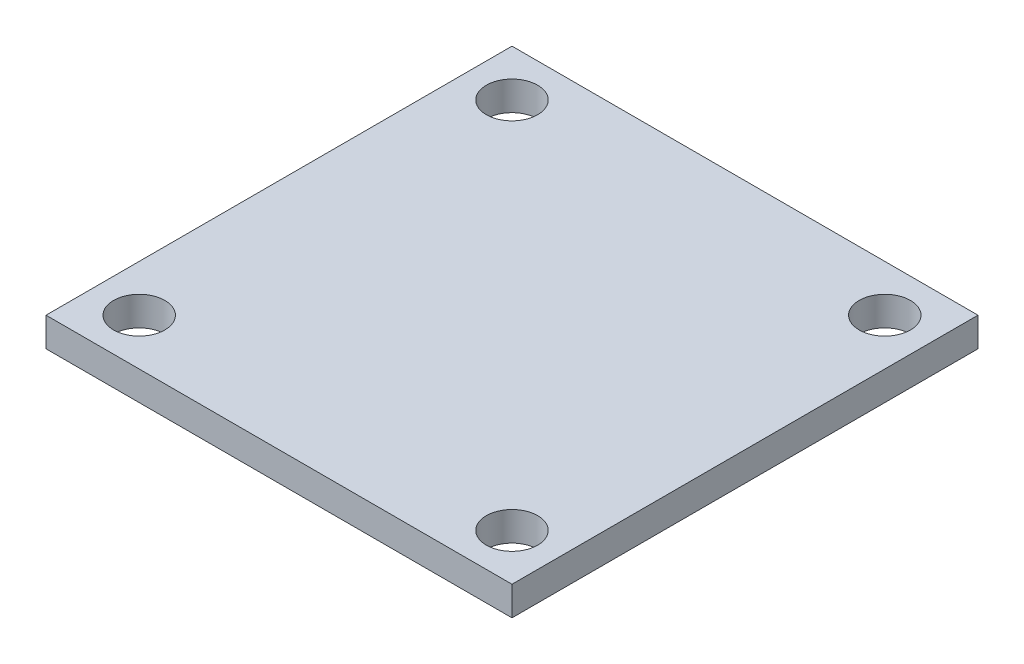
SolidWorks part; units mm, degrees
material "AISI 1045 Aço, trefilado"
ref_plane "Plano frontal" through (0, 0, 0) normal (0, 0, 1) x (1, 0, 0)
ref_plane "Plano superior" through (0, 0, 0) normal (0, 1, 0) x (1, 0, 0)
ref_plane "Plano direito" through (0, 0, 0) normal (1, 0, 0) x (0, 0, -1)
sketch "Esboço1" plane through (0, 0, 0) normal (0, 1, 0) x (1, 0, 0)
  line L1 (-100, 100) -> (100, 100)
  line L2 (-100, 100) -> (-100, -100)
  line L3 (-100, -100) -> (100, -100)
  line L4 (100, 100) -> (100, -100)
  line L5 (-100, 100) -> (100, -100) construction
  line L6 (-100, -100) -> (100, 100) construction
  point P0 (0, 0)
  dimension "D1" = 200
  dimension "D2" = 200
extrude "Ressalto-extrusão1" add sketch "Esboço1" along normal blind 12.5
sketch "Esboço2" plane through (0, 12.5, 0) normal (0, 1, 0) x (1, 0, 0)
  line L0 (100, 100) -> (-100, 100) construction
  line L1 (-100, 100) -> (-100, -100) construction
  circle A0 centre (-80, 80) radius 11
  dimension "D1" = 22
  dimension "D2" = 20
  dimension "D3" = 20
extrude "Corte-extrusão1" cut sketch "Esboço2" against normal through all
pattern_linear "Padrão linear1" count 2 spacing 160 along (1, 0, 0) count 2 spacing 160 along (0, 0, 1) of "Corte-extrusão1"
